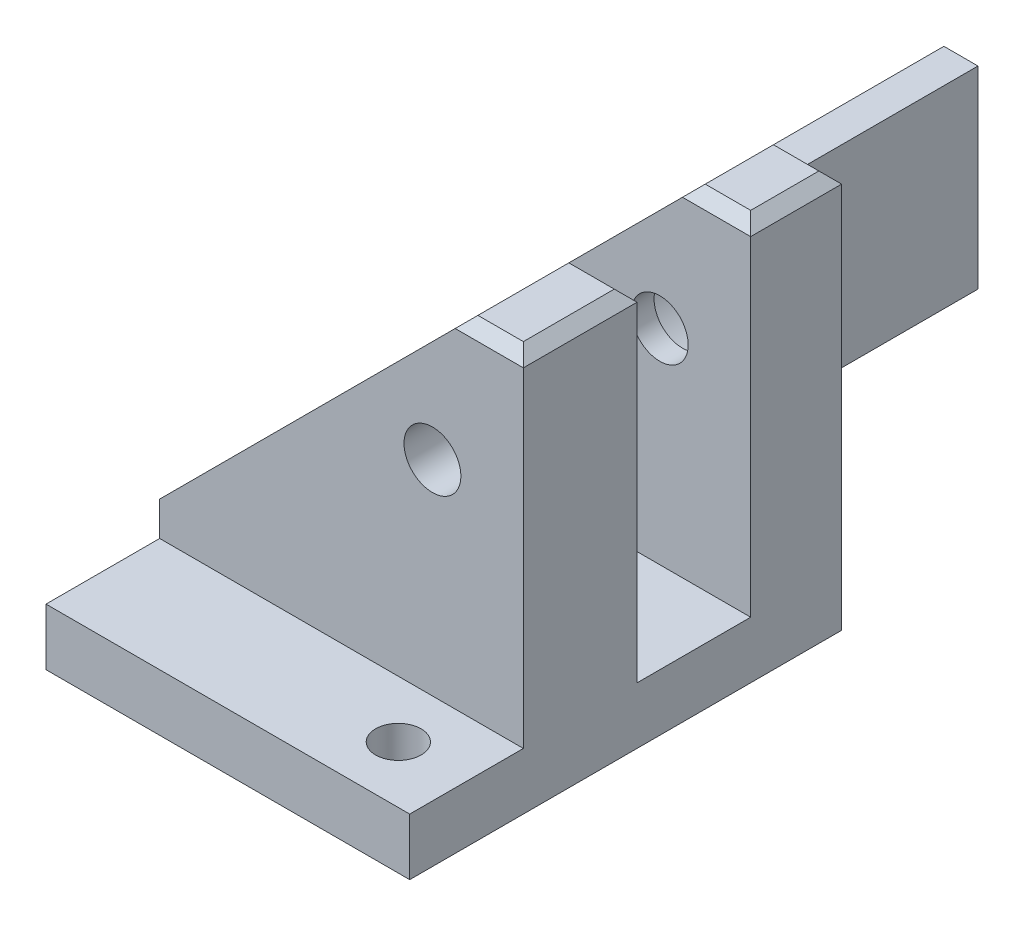
SolidWorks part; units mm, degrees
material "1350 合金"
ref_plane "前视基准面" through (0, 0, 0) normal (0, 0, 1) x (1, 0, 0)
ref_plane "上视基准面" through (0, 0, 0) normal (0, 1, 0) x (1, 0, 0)
ref_plane "右视基准面" through (0, 0, 0) normal (1, 0, 0) x (0, 0, -1)
sketch "草图1" plane through (0, 0, 0) normal (0, 0, 1) x (1, 0, 0)
  line L0 (0, 0) -> (50, 0)
  line L1 (50, 0) -> (50, 30)
  line L2 (50, 30) -> (30, 30)
  line L3 (30, 30) -> (0, 0)
  dimension "D1" = 30
  dimension "D2" = 50
  dimension "D3" = 135
extrude "拉伸1" add sketch "草图1" along normal blind 70
sketch "草图3" plane through (0, 0, 70) normal (0, 0, 1) x (1, 0, 0)
  line L0 (0, 0) -> (50, 0) construction
  line L1 (50, 30) -> (40, 30)
  line L2 (50, 30) -> (50, 0)
  line L3 (50, 0) -> (40, 0)
  line L4 (40, 30) -> (40, 0)
  dimension "D1" = 10
extrude "切除-拉伸2" cut sketch "草图3" against normal through all
sketch "草图4" plane through (0, 0, 70) normal (0, 0, 1) x (1, 0, 0)
  line L0 (0, 0) -> (8, 8)
  line L1 (30, 30) -> (0, 0) construction
  line L2 (8, 8) -> (8, 0)
  line L3 (0, 0) -> (40, 0) construction
  line L4 (8, 0) -> (0, 0)
  line L5 (40, 30) -> (40, 0) construction
  dimension "D1" = 32
extrude "切除-拉伸3" cut sketch "草图4" against normal through all
sketch "草图5" plane through (40, 0, 0) normal (1, 0, 0) x (0, 0, -1)
  line L0 (0, 0) -> (-70, 0) construction
  line L1 (-70, 30) -> (-60, 30)
  line L2 (-70, 30) -> (-70, 5)
  line L3 (-70, 5) -> (-60, 5)
  line L4 (-60, 30) -> (-60, 5)
  line L5 (0, 30) -> (-70, 30) construction
  line L6 (-50, 30) -> (-40, 30)
  line L7 (-50, 30) -> (-50, 5)
  line L8 (-50, 5) -> (-40, 5)
  line L9 (-40, 30) -> (-40, 5)
  dimension "D1" = 5
  dimension "D2" = 10
  dimension "D3" = 10
  dimension "D4" = 10
extrude "切除-拉伸4" cut sketch "草图5" against normal through all
sketch "草图8" plane through (8, 0, 0) normal (-1, 0, 0) x (0, 0, 1)
  line L1 (0, 30) -> (32, 30)
  line L2 (0, 30) -> (0, 5)
  line L3 (0, 5) -> (32, 5)
  line L4 (32, 30) -> (32, 5)
  line L5 (40, 8) -> (40, 30) construction
  dimension "D1" = 8
  dimension "D2" = 25
extrude "切除-拉伸5" cut sketch "草图8" against normal blind 27
sketch "草图9" plane through (35, 0, 0) normal (-1, 0, 0) x (0, 0, 1)
  line L0 (0, 30) -> (32, 30)
  line L1 (32, 30) -> (0, 5)
  line L2 (0, 5) -> (0, 30)
extrude "切除-拉伸6" cut sketch "草图9" against normal through all
sketch "草图10" plane through (0, 0, 32) normal (0, 0, -1) x (-1, 0, 0)
  line L0 (-40, 5) -> (-40, 30) construction
  line L1 (-8, 0) -> (-40, 0) construction
  circle A0 centre (-32, 23) radius 6.3
  dimension "D1" = 12.6
  dimension "D2" = 8
  dimension "D3" = 23
extrude "切除-拉伸7" cut sketch "草图10" against normal blind 6
sketch "草图11" plane through (0, 0, 38) normal (0, 0, -1) x (-1, 0, 0)
  circle A0 centre (-32, 23) radius 2.5
  circle A1 centre (-32, 23) radius 6.3 construction
  dimension "D1" = 5
extrude "切除-拉伸8" cut sketch "草图11" against normal through all
sketch "草图12" plane through (0, 0, 0) normal (0, -1, 0) x (1, 0, 0)
  line L0 (14, 65) -> (14, -5.4427) construction
  line L1 (8, 70) -> (40, 70) construction
  line L2 (35, 0) -> (8, 0) construction
  line L3 (8, 0) -> (8, 32) construction
  circle A0 centre (14, 65) radius 2 construction
  circle A1 centre (14, 10) radius 2
  dimension "D1" = 4
  dimension "D2" = 5
  dimension "D3" = 10
  dimension "D4" = 6
extrude "切除-拉伸9" cut sketch "草图12" against normal through all
sketch "草图13" plane through (0, 0, 0) normal (0, -1, 0) x (1, 0, 0)
  line L1 (8, 70) -> (40, 70) construction
  line L3 (40, 0) -> (40, 70) construction
  circle A0 centre (34, 65) radius 2
  dimension "D1" = 4
  dimension "D2" = 5
  dimension "D3" = 6
extrude "切除-拉伸10" cut sketch "草图13" against normal up to next
sketch "草图14" plane through (35, 0, 0) normal (-1, 0, 0) x (0, 0, 1)
  line L0 (32, 30) -> (32, 5)
  line L1 (32, 5) -> (0, 5)
  line L2 (0, 5) -> (32, 30)
extrude "切除-拉伸11" cut sketch "草图14" against normal blind 10
sketch "草图15" plane through (0, 5, 0) normal (0, 1, 0) x (-1, 0, 0)
  line L0 (-40, 0) -> (-8, 0) construction
  line L1 (-8, 32) -> (-20, 32)
  line L2 (-8, 32) -> (-8, 0)
  line L3 (-8, 0) -> (-20, 0)
  line L4 (-20, 32) -> (-20, 0)
  dimension "D1" = 12
extrude "拉伸2" add sketch "草图15" along normal blind 20
sketch "草图16" plane through (0, 0, 32) normal (0, 0, 1) x (1, 0, 0)
  line L0 (20, 25) -> (20, 20)
  line L1 (20, 20) -> (8, 8)
  line L2 (8, 8) -> (8, 25)
  line L3 (8, 25) -> (20, 25)
extrude "切除-拉伸12" cut sketch "草图16" against normal through all
sketch "草图17" plane through (0, 0, 0) normal (0, 0, -1) x (-1, 0, 0)
  line L0 (-20, 20) -> (-20, 17)
  line L1 (-20, 20) -> (-20, 5) construction
  line L2 (-20, 17) -> (-17, 17)
  line L3 (-8, 8) -> (-20, 20) construction
  line L4 (-17, 17) -> (-20, 20)
  dimension "D1" = 3
extrude "切除-拉伸13" cut sketch "草图17" against normal up to surface (32 mm away) up to face at (25.7, 23, 32)
sketch "草图18" plane through (0, 5, 0) normal (0, 1, 0) x (-1, 0, 0)
  line L1 (-40, 32) -> (-20, 32)
  line L2 (-40, 32) -> (-40, 0)
  line L3 (-40, 0) -> (-20, 0)
  line L4 (-20, 32) -> (-20, 0)
  line L6 (-40, 32) -> (-20, 32) construction
  dimension "D2" = 20
extrude "切除-拉伸14" cut sketch "草图18" against normal through all
sketch "草图20" plane through (0, 0, 60) normal (0, 0, 1) x (1, 0, 0)
  line L0 (30, 30) -> (35, 35)
  line L1 (35, 35) -> (40, 35)
  line L2 (40, 35) -> (40, 30)
  line L4 (8, 8) -> (30, 30) construction
  line L10 (8, 8) -> (8, 5)
  line L11 (8, 5) -> (40, 5)
  line L12 (40, 5) -> (40, 30)
  line L13 (40, 30) -> (30, 30)
  line L14 (30, 30) -> (8, 8)
  line L18 (40, 30) -> (30, 30)
  dimension "D1" = 5
  dimension "D2" = 0
extrude "拉伸3" add sketch "草图20" against normal up to surface (28 mm away) up to face at (25.7, 23, 32)
sketch "草图21" plane through (40, 0, 0) normal (1, 0, 0) x (0, 0, -1)
  line L0 (-32, 35) -> (-60, 35) construction
  line L1 (-50, 30) -> (-40, 30)
  line L2 (-50, 30) -> (-50, 35)
  line L3 (-50, 35) -> (-40, 35)
  line L4 (-40, 30) -> (-40, 35)
  line L5 (-40, 5) -> (-40, 30) construction
extrude "切除-拉伸15" cut sketch "草图21" against normal through all
chamfer "倒角1" distance 1 angle 45 4 edges at (37.5, 35, 40) (37.5, 35, 32) (37.5, 35, 50) (37.5, 35, 60)
chamfer "倒角2" distance 1 angle 45 2 edges at (40, 35, 36) (40, 35, 55)
sketch "草图22" plane through (0, 5, 0) normal (0, -1, 0) x (1, 0, 0)
  circle A0 centre (14, 10) radius 2
extrude "切除-拉伸16" cut sketch "草图22" against normal blind 20
